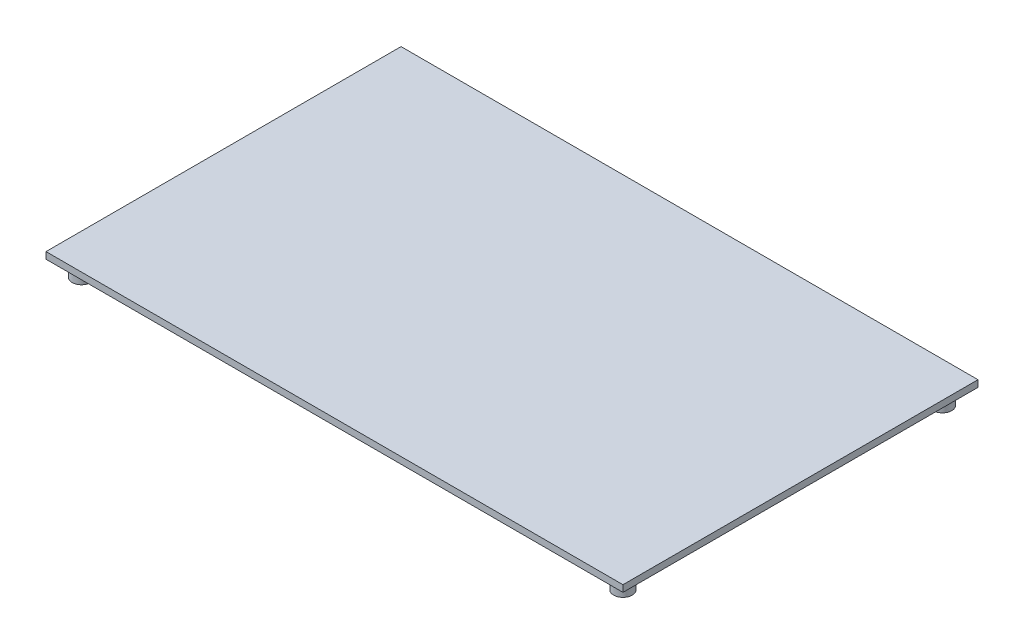
SolidWorks part; units mm, degrees
ref_plane "Front Plane" through (0, 0, 0) normal (0, 0, 1) x (1, 0, 0)
ref_plane "Top Plane" through (0, 0, 0) normal (0, 1, 0) x (1, 0, 0)
ref_plane "Right Plane" through (0, 0, 0) normal (1, 0, 0) x (0, 0, -1)
sketch "Sketch1" plane through (0, 0, 0) normal (0, 1, 0) x (1, 0, 0)
  line L1 (0, 0) -> (165.1, 0)
  line L2 (0, 0) -> (0, 101.6)
  line L3 (0, 101.6) -> (165.1, 101.6)
  line L4 (165.1, 0) -> (165.1, 101.6)
  dimension "D1" = 165.1
  dimension "D2" = 101.6
extrude "Boss-Extrude1" add sketch "Sketch1" along normal blind 1.905
sketch "Sketch3" plane through (0, 0, 0) normal (0, -1, 0) x (1, 0, 0)
  line L0 (165.1, -101.6) -> (0, -101.6) construction
  line L1 (0, -101.6) -> (0, 0) construction
  line L2 (165.1, 0) -> (165.1, -101.6) construction
  line L3 (0, 0) -> (165.1, 0) construction
  circle A0 centre (5.08, -96.52) radius 2.667
  circle A1 centre (5.08, -5.08) radius 2.667
  circle A2 centre (160.02, -5.08) radius 2.667
  circle A3 centre (160.02, -96.52) radius 2.667
  circle A4 centre (118.11, -83.82) radius 2.667
  circle A5 centre (60.325, -83.82) radius 2.667
  circle A6 centre (60.325, -34.925) radius 2.667
  circle A7 centre (118.11, -34.925) radius 2.667
  dimension "D1" = 5.334
  dimension "D2" = 5.334
  dimension "D3" = 5.334
  dimension "D4" = 5.334
  dimension "D5" = 5.08
  dimension "D6" = 5.08
  dimension "D7" = 5.08
  dimension "D8" = 5.08
  dimension "D9" = 5.08
  dimension "D10" = 5.08
  dimension "D11" = 5.08
  dimension "D12" = 5.08
  dimension "D13" = 5.334
  dimension "D14" = 5.334
  dimension "D16" = 17.78
  dimension "D17" = 5.334
  dimension "D18" = 5.334
  dimension "D19" = 34.925
  dimension "D20" = 34.925
  dimension "D21" = 57.785
  dimension "D22" = 60.325
  dimension "D23" = 60.325
  dimension "D24" = 57.785
  dimension "D15" = 17.78
extrude "Boss-Extrude2" add sketch "Sketch3" along normal blind 4.445
